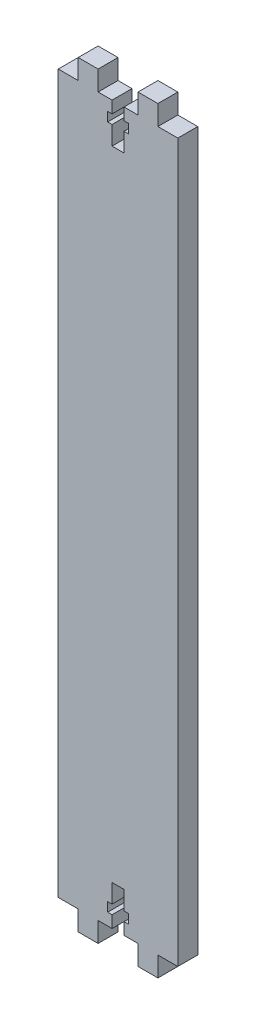
SolidWorks part; units mm, degrees
ref_plane "Front Plane" through (0, 0, 0) normal (0, 0, 1) x (1, 0, 0)
ref_plane "Top Plane" through (0, 0, 0) normal (0, 1, 0) x (1, 0, 0)
ref_plane "Right Plane" through (0, 0, 0) normal (1, 0, 0) x (0, 0, -1)
sketch "Esquisse1" plane through (0, 0, 0) normal (0, 0, 1) x (1, 0, 0)
  line L0 (-10, 5) -> (-15, 5)
  line L1 (-15, 5) -> (-15, 185)
  line L2 (-15, 95) -> (15, 95) construction
  line L3 (15, 185) -> (15, 5)
  line L4 (15, 5) -> (10, 5)
  line L5 (15, 185) -> (10, 185)
  line L6 (-10, 185) -> (-15, 185)
  line B0 (-2.6, 8) -> (-2.6, 10.3)
  line B1 (1.5, 10.3) -> (1.5, 15)
  line B2 (-1.5, 15) -> (-1.5, 10.3)
  line B3 (-2.6, 10.3) -> (-1.5, 10.3)
  line B4 (0, 5) -> (0, 16.2208) construction
  line B5 (-1.5, 5) -> (-5, 5)
  line B6 (-5, 0) -> (-10, 0)
  line B7 (-10, 0) -> (-10, 5)
  line B8 (-5, 0) -> (-5, 5)
  line B9 (1.5, 5) -> (5, 5)
  line B10 (5, 5) -> (5, 0)
  line B11 (5, 0) -> (10, 0)
  line B12 (10, 0) -> (10, 5)
  line B13 (-1.5, 5) -> (1.5, 5) construction
  line B14 (1.5, 5) -> (1.5, 8)
  line B15 (1.5, 10.3) -> (2.6, 10.3)
  line B16 (2.6, 8) -> (1.5, 8)
  line B17 (1.5, 15) -> (-1.5, 15)
  line B18 (-1.5, 8) -> (-2.6, 8)
  line B19 (2.6, 10.3) -> (2.6, 8)
  line B20 (-1.5, 8) -> (-1.5, 5)
  line B21 (0, 15) -> (0, 5) construction
  line B22 (-2.6, 182) -> (-2.6, 179.7)
  line B23 (1.5, 179.7) -> (1.5, 175)
  line B24 (-1.5, 175) -> (-1.5, 179.7)
  line B25 (-2.6, 179.7) -> (-1.5, 179.7)
  line B26 (0, 185) -> (0, 173.7792) construction
  line B27 (-1.5, 185) -> (-5, 185)
  line B28 (-5, 190) -> (-10, 190)
  line B29 (-10, 190) -> (-10, 185)
  line B30 (-5, 190) -> (-5, 185)
  line B31 (1.5, 185) -> (5, 185)
  line B32 (5, 185) -> (5, 190)
  line B33 (5, 190) -> (10, 190)
  line B34 (10, 190) -> (10, 185)
  line B35 (-1.5, 185) -> (1.5, 185) construction
  line B36 (1.5, 185) -> (1.5, 182)
  line B37 (1.5, 179.7) -> (2.6, 179.7)
  line B38 (2.6, 182) -> (1.5, 182)
  line B39 (1.5, 175) -> (-1.5, 175)
  line B40 (-1.5, 182) -> (-2.6, 182)
  line B41 (2.6, 179.7) -> (2.6, 182)
  line B42 (-1.5, 182) -> (-1.5, 185)
  line B43 (0, 175) -> (0, 185) construction
  dimension "D1" = 5
  dimension "D2" = 90
sketch_block_instance "Insert M3 plots ep 5mm-1"
sketch_block "Insert M3 plots ep 5mm" parameters "D1"=10, "D2"=5, "D3"=5
sketch_block_instance "Decoupe Insert M3-4"
sketch_block "Decoupe Insert M3" parameters "D1"=5.2, "D2"=3, "D3"=2.3, "D4"=3, "D5"=10
sketch_block_instance "Insert M3 plots ep 5mm-3"
extrude "Boss.-Extru.1" add sketch "Esquisse1" along normal blind 5 contours L1 L2 L3 L5 B34 B33 B32 B31 B36 B38 B41 B37 B23 B39 B24 B25 B22 B40 B42 B27 B30 B28 B29 L6 | L2 L1 L0 B7 B6 B8 B5 B20 B18 B0 B3 B2 B17 B1 B15 B19 B16 B14 B9 B10 B11 B12 L4 L3
